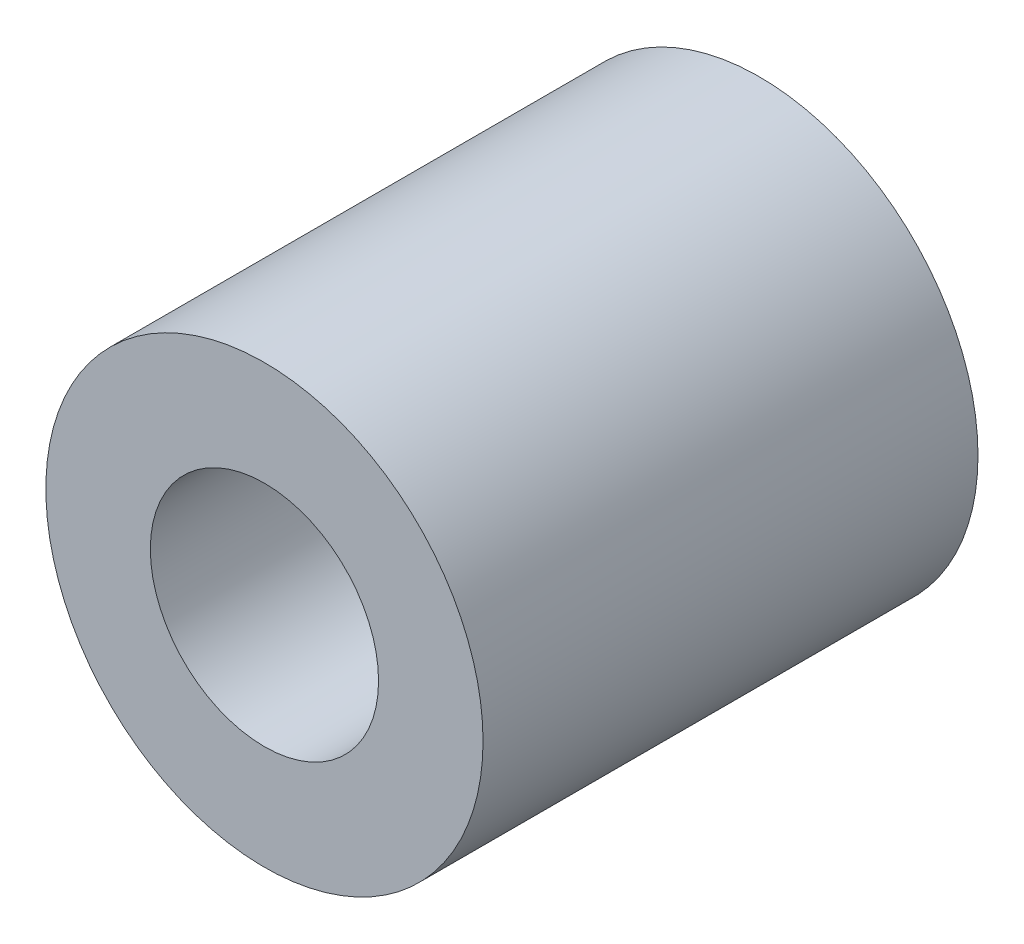
SolidWorks part; units mm, degrees
ref_plane "Front Plane" through (0, 0, 0) normal (0, 0, 1) x (1, 0, 0)
ref_plane "Top Plane" through (0, 0, 0) normal (0, 1, 0) x (1, 0, 0)
ref_plane "Right Plane" through (0, 0, 0) normal (1, 0, 0) x (0, 0, -1)
sketch "Sketch1" plane through (0, 0, 0) normal (0, 0, 1) x (1, 0, 0)
  circle A0 centre (0, 0) radius 7.95
  circle A1 centre (0, 0) radius 4.15
  dimension "D1" = 15.9
  dimension "D2" = 8.3
extrude "Boss-Extrude1" add sketch "Sketch1" along normal blind 18
